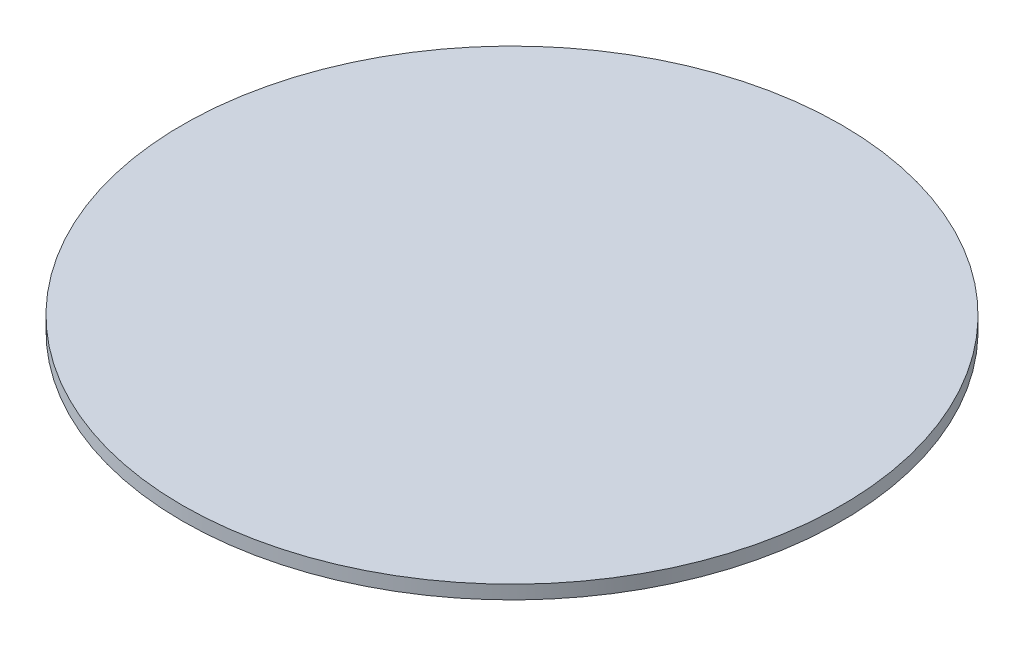
SolidWorks part; units mm, degrees
ref_plane "Front Plane" through (0, 0, 0) normal (0, 0, 1) x (1, 0, 0)
ref_plane "Top Plane" through (0, 0, 0) normal (0, 1, 0) x (1, 0, 0)
ref_plane "Right Plane" through (0, 0, 0) normal (1, 0, 0) x (0, 0, -1)
sketch "Sketch1" plane through (0, 0, 0) normal (0, 1, 0) x (1, 0, 0)
  circle A0 centre (0, 0) radius 14.5
  dimension "D1" = 29
extrude "Boss-Extrude1" add sketch "Sketch1" along normal blind 0.6
